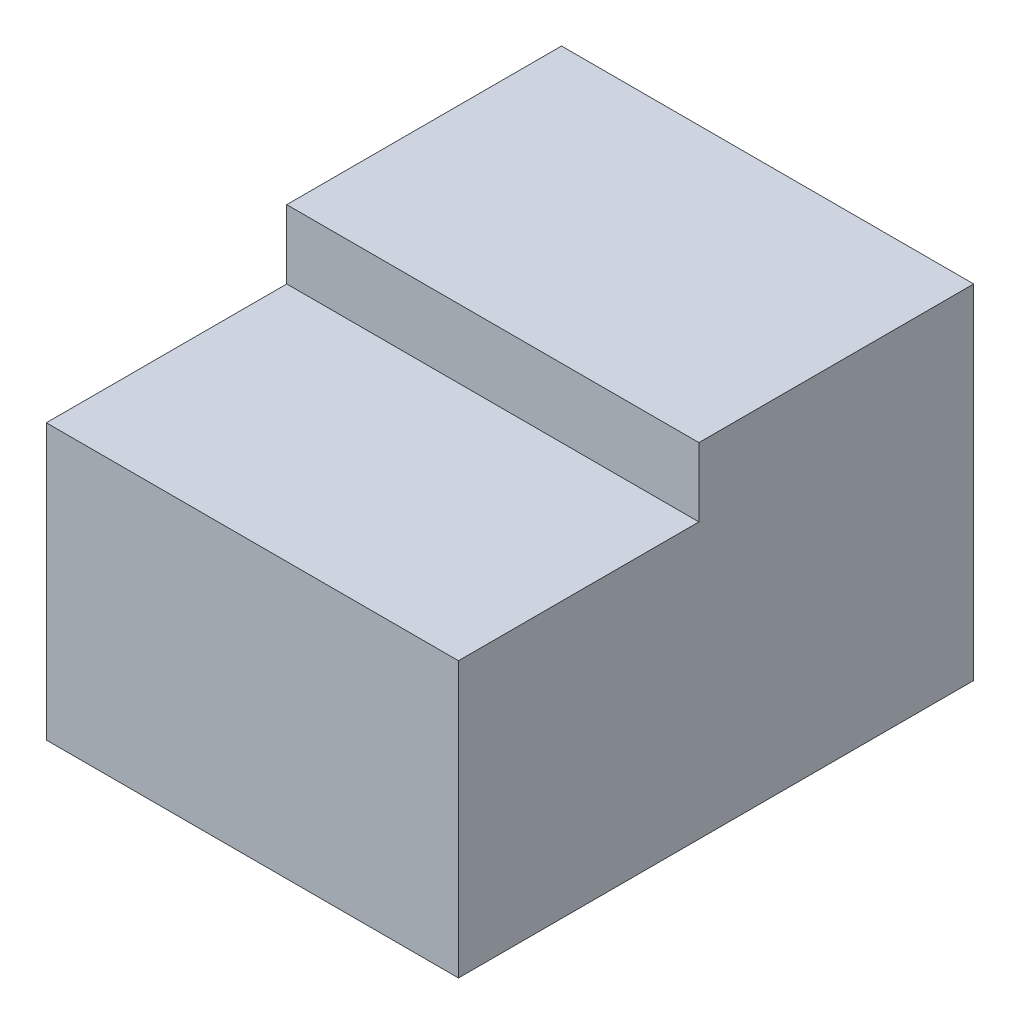
SolidWorks part; units mm, degrees
ref_plane "Front Plane" through (0, 0, 0) normal (0, 0, 1) x (1, 0, 0)
ref_plane "Top Plane" through (0, 0, 0) normal (0, 1, 0) x (1, 0, 0)
ref_plane "Right Plane" through (0, 0, 0) normal (1, 0, 0) x (0, 0, -1)
sketch "Sketch2" plane through (0, 0, 0) normal (1, 0, 0) x (0, 0, -1)
  line L0 (0, 0) -> (-15, 0)
  line L1 (-15, 0) -> (-15, 8)
  line L2 (-15, 8) -> (-8, 8)
  line L3 (-8, 8) -> (-8, 10)
  line L4 (-8, 10) -> (0, 10)
  line L5 (0, 10) -> (0, 0)
  dimension "D1" = 15
  dimension "D2" = 8
  dimension "D3" = 10
  dimension "D4" = 8
extrude "Boss-Extrude1" add sketch "Sketch2" along normal blind 12 contours L0 L1 L2 L3 L4 L5
sketch "Sketch3" plane through (0, 0, 0) normal (0, 0, -1) x (-1, 0, 0)
  line L0 (-12, 10) -> (-12, 0) construction
  line L1 (-12, 10) -> (0, 10) construction
  line L2 (-3.6906, 9) -> (-8.3094, 9)
  line L3 (-8.3094, 9) -> (-10.6188, 5)
  line L4 (-10.6188, 5) -> (-8.3094, 1)
  line L5 (-8.3094, 1) -> (-3.6906, 1)
  line L6 (-3.6906, 1) -> (-1.3812, 5)
  line L7 (-1.3812, 5) -> (-3.6906, 9)
  circle A0 centre (-6, 5) radius 4.6188 construction
  dimension "D1" = 6
  dimension "D2" = 5
  dimension "D3" = 8
  dimension "D4" = 8
extrude "Cut-Extrude1" cut sketch "Sketch3" against normal blind 5
sketch "Sketch4" plane through (0, 0, 0) normal (0, -1, 0) x (1, 0, 0)
  line L0 (12, 0) -> (12, 15) construction
  line L2 (12, 15) -> (0, 15) construction
  line L3 (3.6906, 6) -> (8.3094, 6)
  line L4 (8.3094, 6) -> (10.6188, 10)
  line L5 (10.6188, 10) -> (8.3094, 14)
  line L6 (8.3094, 14) -> (3.6906, 14)
  line L7 (3.6906, 14) -> (1.3812, 10)
  line L8 (1.3812, 10) -> (3.6906, 6)
  circle A0 centre (6, 10) radius 4.6188 construction
  dimension "D1" = 6
  dimension "D2" = 5
  dimension "D3" = 8
  dimension "D4" = 8
extrude "Cut-Extrude2" cut sketch "Sketch4" against normal blind 5
